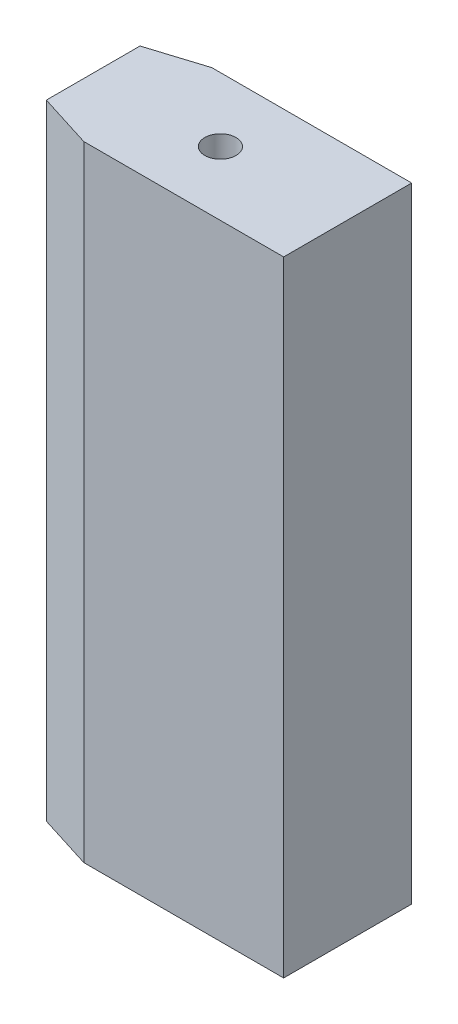
SolidWorks part; units mm, degrees
ref_plane "Front Plane" through (0, 0, 0) normal (0, 0, 1) x (1, 0, 0)
ref_plane "Top Plane" through (0, 0, 0) normal (0, 1, 0) x (1, 0, 0)
ref_plane "Right Plane" through (0, 0, 0) normal (1, 0, 0) x (0, 0, -1)
sketch "Sketch1" plane through (0, 0, 0) normal (0, 1, 0) x (1, 0, 0)
  line L0 (0, 0) -> (0, 8.2)
  line L1 (0, 8.2) -> (-12.8, 8.2)
  line L2 (0, 0) -> (-12.8, 0)
  line L3 (0, 4.1) -> (-16.3, 4.1)
  line L4 (-16.3, 4.1) -> (-16.3, 7.1)
  line L5 (-16.3, 7.1) -> (-12.8, 8.2)
  line L6 (-16.3, 4.1) -> (-16.3, 1.1)
  line L7 (-16.3, 1.1) -> (-12.8, 0)
  dimension "D1" = 8.2
  dimension "D2" = 12.8
  dimension "D3" = 12.8
  dimension "D4" = 16.3
  dimension "D5" = 3
  dimension "D6" = 3
extrude "Boss-Extrude1" add sketch "Sketch1" along normal blind 40 contours L5 L4 L3 L0 L1 | L6 L7 L2 L0 L3
sketch "Sketch2" plane through (0, 40, 0) normal (0, 1, 0) x (1, 0, 0)
  line L0 (0, 4.1) -> (-16.3, 4.1)
  line L1 (0, 0) -> (0, 8.2) construction
  line L2 (-16.3, 1.1) -> (-16.3, 7.1) construction
  circle A0 centre (-8.15, 4.1) radius 1
  dimension "D1" = 2
extrude "Cut-Extrude1" cut sketch "Sketch2" against normal through all contours L0 A0 | L0 A0
